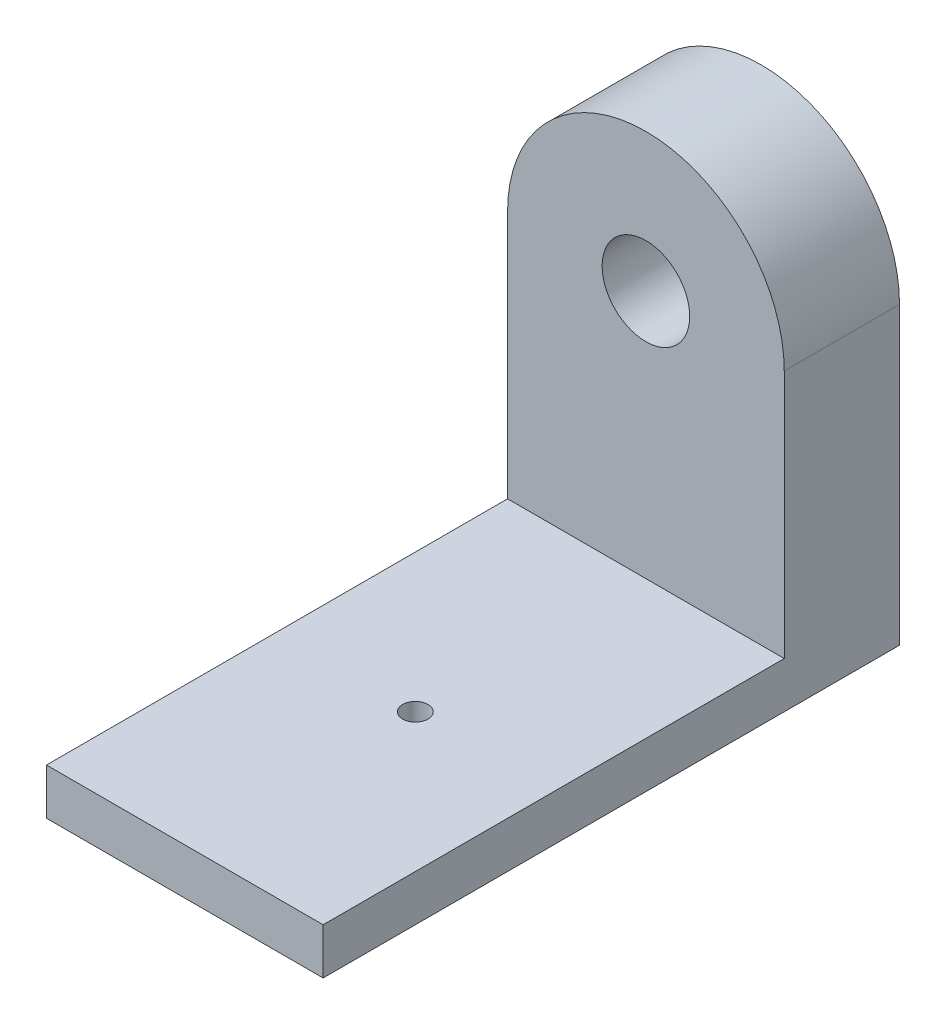
SolidWorks part; units mm, degrees
ref_plane "Front Plane" through (0, 0, 0) normal (0, 0, 1) x (1, 0, 0)
ref_plane "Top Plane" through (0, 0, 0) normal (0, 1, 0) x (1, 0, 0)
ref_plane "Right Plane" through (0, 0, 0) normal (1, 0, 0) x (0, 0, -1)
sketch "Sketch1" plane through (0, 0, 0) normal (0, 1, 0) x (1, 0, 0)
  line L1 (0, 0) -> (60, 0)
  line L2 (0, 0) -> (0, 125)
  line L3 (0, 125) -> (60, 125)
  line L4 (60, 0) -> (60, 125)
  dimension "D1" = 125
  dimension "D2" = 60
extrude "Boss-Extrude1" add sketch "Sketch1" along normal blind 10
sketch "Sketch2" plane through (0, 0, -125) normal (0, 0, -1) x (-1, 0, 0)
  line L0 (-60, 0) -> (0, 0) construction
  line L1 (-60, 10) -> (0, 10)
  line L2 (-60, 10) -> (-60, 64)
  line L3 (0, 10) -> (0, 0) construction
  line L4 (0, 10) -> (0, 64)
  arc A0 (0, 64) -> (-60, 64) centre (-30, 64) ccw
  circle A1 centre (-30, 64) radius 9.5
  dimension "D2" = 19
  dimension "D1" = 64
extrude "Boss-Extrude2" add sketch "Sketch2" against normal blind 25
sketch "Sketch3" plane through (0, 10, 0) normal (0, 1, 0) x (1, 0, 0)
  line L0 (60, 0) -> (60, 100) construction
  line L1 (0, 0) -> (60, 0) construction
  circle A0 centre (30, 50) radius 2.75
  dimension "D1" = 5.5
  dimension "D2" = 30
  dimension "D3" = 50
extrude "Cut-Extrude1" cut sketch "Sketch3" against normal up to next
